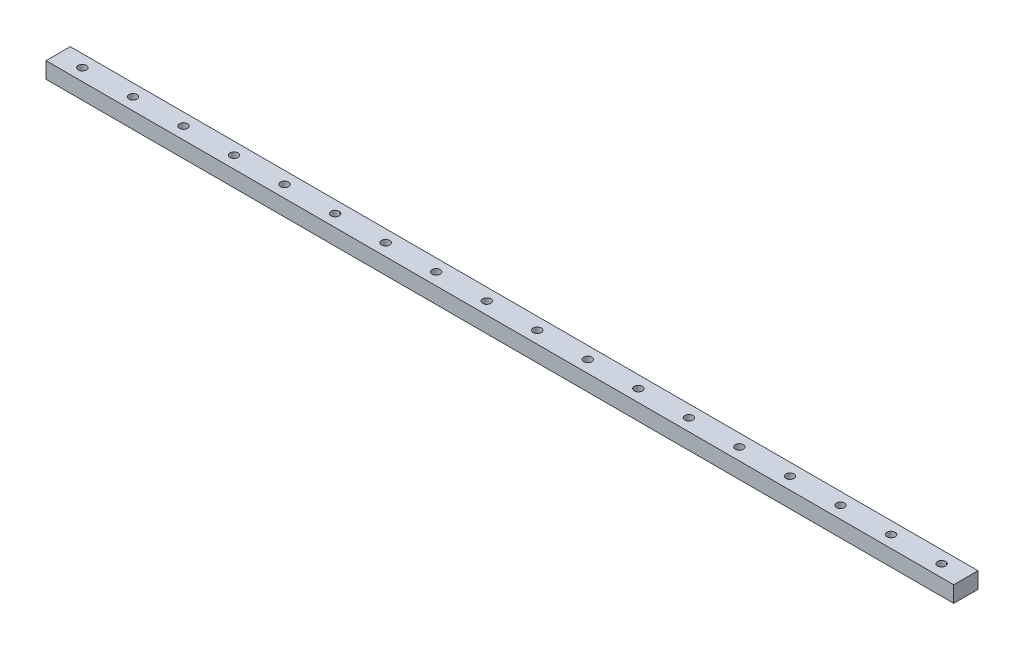
SolidWorks part; units mm, degrees
ref_plane "Front Plane" through (0, 0, 0) normal (0, 0, 1) x (1, 0, 0)
ref_plane "Top Plane" through (0, 0, 0) normal (0, 1, 0) x (1, 0, 0)
ref_plane "Right Plane" through (0, 0, 0) normal (1, 0, 0) x (0, 0, -1)
sketch "Sketch1" plane through (0, 0, 0) normal (0, 1, 0) x (1, 0, 0)
  line L1 (0, 0) -> (449, 0)
  line L2 (0, 0) -> (0, 12)
  line L3 (0, 12) -> (449, 12)
  line L4 (449, 0) -> (449, 12)
  circle A0 centre (12, 6) radius 2
  circle A1 centre (37, 6) radius 2
  circle A2 centre (62, 6) radius 2
  circle A3 centre (87, 6) radius 2
  circle A4 centre (112, 6) radius 2
  circle A5 centre (137, 6) radius 2
  circle A6 centre (162, 6) radius 2
  circle A7 centre (187, 6) radius 2
  circle A8 centre (212, 6) radius 2
  circle A9 centre (237, 6) radius 2
  circle A10 centre (262, 6) radius 2
  circle A11 centre (287, 6) radius 2
  circle A12 centre (312, 6) radius 2
  circle A13 centre (337, 6) radius 2
  circle A14 centre (362, 6) radius 2
  circle A15 centre (387, 6) radius 2
  circle A16 centre (412, 6) radius 2
  circle A17 centre (437, 6) radius 2
  point P8 (0, 6)
  dimension "D3" = 4
  dimension "D1" = 12
  dimension "D2" = 12
  dimension "D4" = 18
  dimension "D5" = 12
extrude "Boss-Extrude1" add sketch "Sketch1" along normal blind 8
